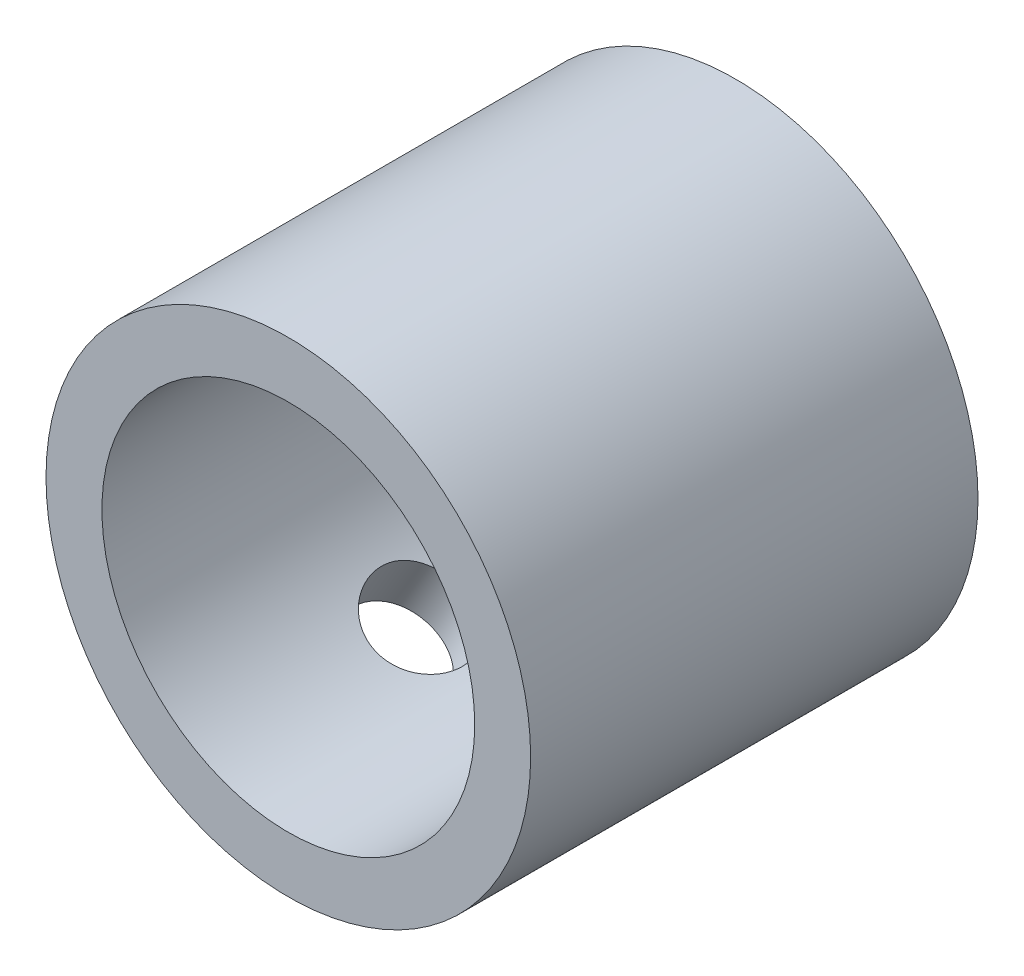
SolidWorks part; units mm, degrees
ref_plane "Front Plane" through (0, 0, 0) normal (0, 0, 1) x (1, 0, 0)
ref_plane "Top Plane" through (0, 0, 0) normal (0, 1, 0) x (1, 0, 0)
ref_plane "Right Plane" through (0, 0, 0) normal (1, 0, 0) x (0, 0, -1)
sketch "Sketch1" plane through (0, 0, 0) normal (0, 0, 1) x (1, 0, 0)
  circle A0 centre (0, 0) radius 5
  circle A1 centre (0, 0) radius 6.5
  dimension "D1" = 13
  dimension "D2" = 10
extrude "Boss-Extrude1" add sketch "Sketch1" along normal blind 12
ref_plane "Plane1" through (0, 0, 6) normal (0, 0, 1) x (1, 0, 0)
sketch "Sketch2" plane through (0, 0, 6) normal (0, 0, 1) x (1, 0, 0)
  line L0 (0, 0) -> (-4.3606, -7.5528) construction
  line L1 (0, 0) -> (0, -8.1854) construction
  line L2 (-0.7646, -3.8244) -> (-2.7065, -7.1878)
  line L3 (-2.7065, -7.1878) -> (-3.789, -6.5628)
  line L4 (-3.789, -6.5628) -> (-1.8472, -3.1994)
  line L5 (-1.8472, -3.1994) -> (-0.7646, -3.8244)
  dimension "D1" = 30
  dimension "D2" = 1.25
revolve "Cut-Revolve1" cut sketch "Sketch2" angle 360 about L4
